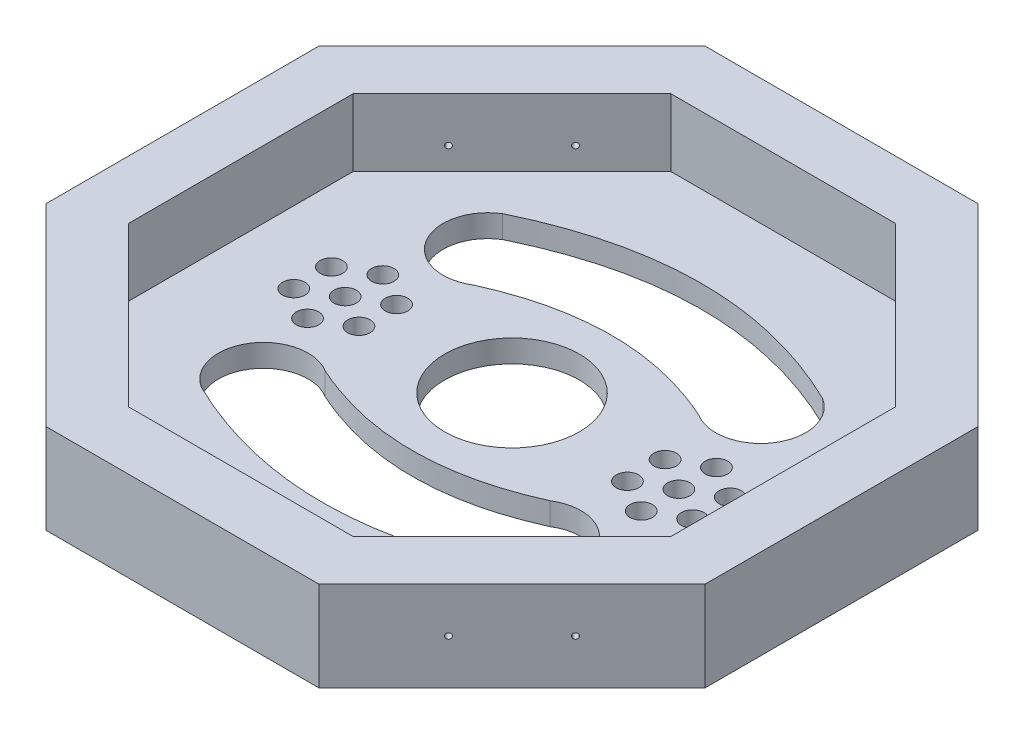
SolidWorks part; units mm, degrees
ref_plane "Plano frontal" through (0, 0, 0) normal (0, 0, 1) x (1, 0, 0)
ref_plane "Plano superior" through (0, 0, 0) normal (0, 1, 0) x (1, 0, 0)
ref_plane "Plano direito" through (0, 0, 0) normal (1, 0, 0) x (0, 0, -1)
sketch "Esboço1" plane through (0, 0, 0) normal (0, 1, 0) x (1, 0, 0)
  line L24 (146.6822, -60.7578) -> (146.6822, 60.7578)
  line L37 (60.7578, 146.6822) -> (-60.7578, 146.6822)
  line L38 (-60.7578, 146.6822) -> (-146.6822, 60.7578)
  line L39 (-146.6822, 60.7578) -> (-146.6822, -60.7578)
  line L40 (-146.6822, -60.7578) -> (-60.7578, -146.6822)
  line L41 (-60.7578, -146.6822) -> (60.7578, -146.6822)
  line L42 (60.7578, -146.6822) -> (146.6822, -60.7578)
  line L43 (146.6822, 60.7578) -> (60.7578, 146.6822)
  circle A0 centre (0, 0) radius 146.6822 construction
  point P1 (-146.6822, 0)
extrude "Ressalto-extrusão1" add sketch "Esboço1" along normal blind 40
sketch "Esboço2" plane through (0, 40, 0) normal (0, 1, 0) x (1, 0, 0)
  line L1 (120.7107, 50) -> (50, 120.7107)
  line L2 (50, 120.7107) -> (-50, 120.7107)
  line L3 (-50, 120.7107) -> (-120.7107, 50)
  line L4 (-120.7107, 50) -> (-120.7107, -50)
  line L5 (-120.7107, -50) -> (-50, -120.7107)
  line L6 (-50, -120.7107) -> (50, -120.7107)
  line L7 (50, -120.7107) -> (120.7107, -50)
  line L8 (120.7107, -50) -> (120.7107, 50)
  circle A0 centre (0, 0) radius 120.7107 construction
  point P1 (-120.7107, 0)
  dimension "D1" = 100
extrude "Corte-extrusão2" cut sketch "Esboço2" against normal blind 25 from offset 5 offset against normal yes
sketch "Esboço3" plane through (0, 40, 0) normal (0, 1, 0) x (1, 0, 0)
  line L1 (120.7107, 50) -> (50, 120.7107)
  line L2 (50, 120.7107) -> (-50, 120.7107)
  line L3 (-50, 120.7107) -> (-120.7107, 50)
  line L4 (-120.7107, 50) -> (-120.7107, -50)
  line L5 (-120.7107, -50) -> (-50, -120.7107)
  line L6 (-50, -120.7107) -> (50, -120.7107)
  line L7 (50, -120.7107) -> (120.7107, -50)
  line L8 (120.7107, -50) -> (120.7107, 50)
  circle A0 centre (0, 0) radius 120.7107 construction
  point P1 (0, 0)
  point P12 (-120.7107, 0)
  dimension "D1" = 100
extrude "Corte-extrusão3" cut sketch "Esboço3" against normal blind 25
sketch "Esboço4" plane through (0, 10, 0) normal (0, 1, 0) x (1, 0, 0)
  line L0 (-120.7107, 50) -> (-60.7107, 50) construction
  line L1 (-120.7107, 50) -> (-120.7107, -50) construction
  line L2 (0, -22) -> (0, 22) construction
  line L3 (0, 84.404) -> (0, 44.404) construction
  line L4 (-22, 0) -> (22, 0) construction
  circle A0 centre (0, 0) radius 30
  arc A1 (-71.1731, 67.0452) -> (-50.0817, 33.0582) centre (-60.7107, 50) ccw
  arc A5 (71.1731, 67.0452) -> (50.0817, 33.0582) centre (60.7107, 50) cw
  arc A6 (-71.1731, -67.0452) -> (-50.0817, -33.0582) centre (-60.7107, -50) cw
  arc A7 (71.1731, -67.0452) -> (50.0817, -33.0582) centre (60.7107, -50) ccw
  circle A11 centre (-74.2664, 16.749) radius 5
  circle A13 centre (-59.7613, 8.3745) radius 5
  circle A14 centre (-59.7613, -8.3745) radius 5
  circle A15 centre (-74.2664, -16.749) radius 5
  circle A16 centre (-88.7715, -8.3745) radius 5
  circle A17 centre (-88.7715, 8.3745) radius 5
  circle A18 centre (-74.2664, 0) radius 5
  circle A19 centre (74.2664, 0) radius 5
  circle A20 centre (88.7715, 8.3745) radius 5
  circle A21 centre (88.7715, -8.3745) radius 5
  circle A22 centre (74.2664, -16.749) radius 5
  circle A23 centre (59.7613, -8.3745) radius 5
  circle A24 centre (59.7613, 8.3745) radius 5
  circle A25 centre (74.2664, 16.749) radius 5
  spline S0 degree 2 poles (-71.1731, 67.0452) (0, 101.7629) (71.1731, 67.0452) knots 0 0 0 1 1 1
  spline S1 degree 2 poles (-50.0817, 33.0582) (0, 55.7499) (50.0817, 33.0582) knots 0 0 0 1 1 1
  spline S2 degree 2 poles (-71.1731, -67.0452) (0, -101.7629) (71.1731, -67.0452) knots 0 0 0 1 1 1
  spline S3 degree 2 poles (-50.0817, -33.0582) (0, -55.7499) (50.0817, -33.0582) knots 0 0 0 1 1 1
  point P46 (-74.2664, 0)
  point P58 (74.2664, 0)
  point P59 (-78.7437, 68.3159)
  point P60 (52.7055, 41.2928)
  point P61 (-50.0817, 33.0582)
  dimension "D1" = 40
  dimension "D5" = 60
  dimension "D6" = 10
  dimension "D2" = 90
  dimension "D3" = 60
  dimension "D4" = 40
  dimension "D7" = 6
extrude "Corte-extrusão4" cut sketch "Esboço4" against normal blind 10
hole_wizard "Broca de rosquear para tarraxa de M31" positions "Esboço7" profile "Esboço8" hole size "M3" standard "ISO" end condition through all
sketch "Esboço7" plane through (103.72, 0, 103.72) normal (0.7071, 0, 0.7071) x (0.7071, 0, -0.7071)
  line L0 (-20, 20) -> (20, 20) construction
  line L1 (-60.7578, 0) -> (60.7578, 0) construction
  point P0 (-20, 20)
  point P2 (20, 20)
  point P8 (0, 20)
  dimension "D1" = 40
  dimension "D2" = 20
sketch "Esboço8" plane through (89.5778, 20, 117.8621) normal (0, 1, 0) x (0.7071, 0, -0.7071)
  line L0 (0, 0) -> (0, 354.1222)
  line L1 (0, 354.1222) -> (1.25, 354.1222)
  line L2 (1.25, 354.1222) -> (1.25, 0)
  line L5 (1.25, 0) -> (0, 0)
  line L11 (0, -6.35) -> (0, 107.95) construction
  dimension "Thru Hole Dia." = 2.5
  dimension "Thru Hole Depth" = 354.1222
hole_wizard "Broca de rosquear para tarraxa de M32" positions "Esboço9" profile "Esboço10" hole size "M3" standard "ISO" end condition through all
sketch "Esboço9" plane through (-103.72, 0, 103.72) normal (-0.7071, 0, 0.7071) x (0.7071, 0, 0.7071)
  line L0 (-20, 20) -> (20, 20) construction
  line L2 (-60.7578, 0) -> (60.7578, 0) construction
  point P0 (-20, 20)
  point P2 (20, 20)
  point P9 (0, 20)
  dimension "D1" = 20
  dimension "D2" = 40
sketch "Esboço10" plane through (-117.8621, 20, 89.5778) normal (0, 1, 0) x (0.7071, 0, 0.7071)
  line L0 (0, 0) -> (0, 354.1222)
  line L1 (0, 354.1222) -> (1.25, 354.1222)
  line L2 (1.25, 354.1222) -> (1.25, 0)
  line L5 (1.25, 0) -> (0, 0)
  line L11 (0, -6.35) -> (0, 107.95) construction
  dimension "Thru Hole Dia." = 2.5
  dimension "Thru Hole Depth" = 354.1222
